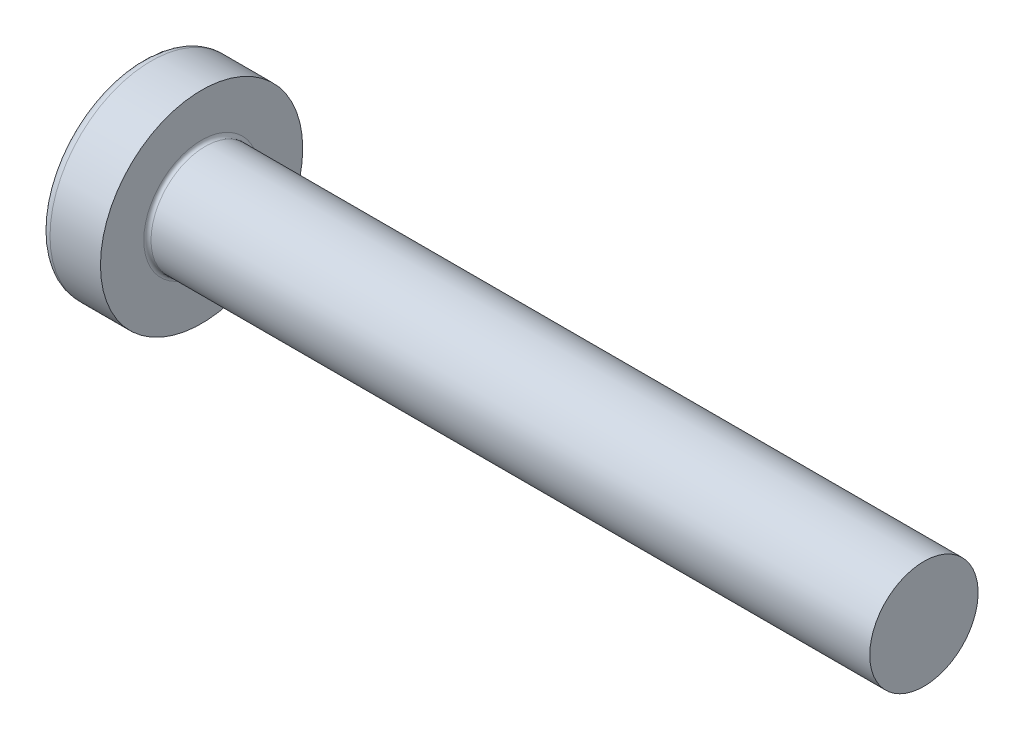
SolidWorks part; units mm, degrees
ref_plane "Plane1" through (0, 0, 0) normal (0, 0, 1) x (1, 0, 0)
ref_plane "Plane2" through (0, 0, 0) normal (0, 1, 0) x (1, 0, 0)
ref_plane "Plane3" through (0, 0, 0) normal (1, 0, 0) x (0, 0, -1)
sketch "BodySke" plane through (0, 0, 0) normal (0, 0, 1) x (1, 0, 0)
  line L0 (2.4, 1.5) -> (2.4, 2.8)
  line L1 (2.65, 6.35) -> (2.65, -3.175) construction
  line L2 (-25.4, 0) -> (127, 0) construction
  line L3 (22.4, 0) -> (0, 0)
  line L4 (2.4, 1.5) -> (22.4, 1.5)
  line L5 (22.4, 1.5) -> (22.4, 0)
  line L6 (1.0035, 2.8) -> (2.4, 2.8)
  line L8 (2.4, 6.35) -> (2.4, -3.175) construction
  arc A0 (0.7754, 2.6744) -> (0, 0) centre (5, 0) ccw
  arc A2 (0.7754, 2.6744) -> (1.0035, 2.8) centre (1.0035, 2.53) cw
  dimension "Head_crown_rad" = 5
  dimension "Head_fillet_rad" = 0.27
  dimension "Length" = 20
  dimension "Head_ht" = 2.4
  dimension "Head_dia" = 5.6
  dimension "Advance" = 0.5
  dimension "Thread_nom" = 20
  dimension "Diameter" = 3
revolve "Base-Revolve" add sketch "BodySke"
cosmetic thread "ThreadCosmetic" [suppressed]
fillet "Fillet1" radius 0.1 1 edges at (2.4, 0, 1.5)
sketch "Sketch3" plane through (0, 0, 0) normal (1, 0, 0) x (0, 0, -1)
  line L0 (0.37, -1.4) -> (-0.37, -1.4)
  line L1 (0.37, -1.4) -> (0.37, 1.4)
  line L2 (-0.37, 1.4) -> (0.37, 1.4)
  line L3 (-0.37, 1.4) -> (-0.37, -1.4)
  dimension "Cross_dia" = 2.8
  dimension "D1" = 1.4
  dimension "Cross_width" = 0.74
  dimension "D2" = 0.37
ref_plane "Plane4" through (1.75, 0, 0) normal (1, 0, 0) x (0, 0, -1)
sketch "Sketch4" plane through (1.75, 0, 0) normal (1, 0, 0) x (0, 0, -1)
  line L0 (0.37, -0.5275) -> (-0.37, -0.5275)
  line L1 (0.37, -0.5275) -> (0.37, 0.5275)
  line L2 (-0.37, 0.5275) -> (0.37, 0.5275)
  line L3 (-0.37, 0.5275) -> (-0.37, -0.5275)
  dimension "D1" = 0.74
  dimension "D2" = 1.055
  dimension "D3" = 0.37
  dimension "D4" = 0.5275
loft "Recess" cut profiles "Sketch3", "Sketch4"
pattern_circular "RecPat" count 2 every 90 about axis through (0, 0, 0) along (1, 0, 0) of "Recess"
sketch "RecCorSke" plane through (0, 0, 0) normal (0, 0, 1) x (1, 0, 0)
  line L0 (-3.175, 0) -> (15.875, 0) construction
  line L1 (-25.4, 0) -> (127, 0) construction
  line L2 (0, 0) -> (0, 0.6784)
  line L3 (0, 0.6784) -> (1.75, 0.556)
  line L4 (1.75, 0.556) -> (1.9307, 0)
  line L5 (1.9307, 0) -> (0, 0)
  dimension "Diameter" = 1.112
  dimension "Depth" = 1.75
  dimension "Draft_angle" = 4
  dimension "Bottom_angle" = 18
revolve "RecessCore" cut sketch "RecCorSke" angle 360 about L0
sketch "ThdSchSke" plane through (0, 0, 0) normal (0, 0, 1) x (1, 0, 0)
  line L0 (3.4, -1.2195) -> (3.2036, -1.5)
  line L1 (3.4, -1.2195) -> (3.5964, -1.5)
  line L2 (3.5964, -1.5) -> (3.5964, -1.875)
  line L3 (-3.175, 0) -> (5.1513, 0) construction
  line L5 (3.5964, -1.875) -> (3.2036, -1.875)
  line L6 (3.2036, -1.875) -> (3.2036, -1.5)
  dimension "Diameter" = 3
  dimension "SideAngle" = 55
  dimension "VeeAngle" = 70
  dimension "Thread_minor" = 2.439
  dimension "Overcut" = 3.75
  dimension "Start" = 3.4
revolve "ThreadSchematic" [suppressed] cut sketch "ThdSchSke" angle 360 about L3
pattern_linear "ThdSchPat" [suppressed]
equation "\"D1@Sketch3\" = \"Cross_dia@Sketch3\" / 2"
equation "\"D2@Sketch3\" = \"Cross_width@Sketch3\" / 2"
equation "\"Depth@RecCorSke\" = \"Cross_depth@Plane4\""
equation "\"D1@Sketch4\" = \"Cross_width@Sketch3\""
equation "\"D2@Sketch4\" = \"Cross_dia@Sketch3\" - 2.0 * \"Cross_depth@Plane4\" * tan(26.5  * 0.017453292)"
equation "\"D3@Sketch4\" = \"D1@Sketch4\" / 2"
equation "\"D4@Sketch4\" = \"D2@Sketch4\" / 2"
equation "\"Thread_length@ThreadCosmetic\" = ((sgn( (\"Length@BodySke\" - \"Advance@BodySke\" * 2.0 ) - \"Thread_nom@BodySke\" )-1)*( (\"Length@BodySke\" - \"Advance@BodySke\" * 2.0 ) - \"Thread_nom@BodySke\" ))/-2+ \"Thread_nom@BodySke\""
equation "\"Thread_minor@ThdSchSke\" = \"Thread_minor@ThreadCosmetic\""
equation "\"Diameter@ThdSchSke\" = \"Diameter@BodySke\""
equation "\"Overcut@ThdSchSke\" = \"Diameter@BodySke\" * 1.25"
equation "\"Start@ThdSchSke\" = \"Head_ht@BodySke\" + \"Length@BodySke\" - \"Thread_length@ThreadCosmetic\"  '---Non-countersunk---"
equation "\"Num_threads@ThdSchPat\" = int( \"Thread_length@ThreadCosmetic\" / \"Advance@BodySke\" + 0.999 )  + 1"
equation "\"Advance@ThdSchPat\" = \"Thread_length@ThreadCosmetic\" /  (\"Num_threads@ThdSchPat\" - 1) 'relax it"
